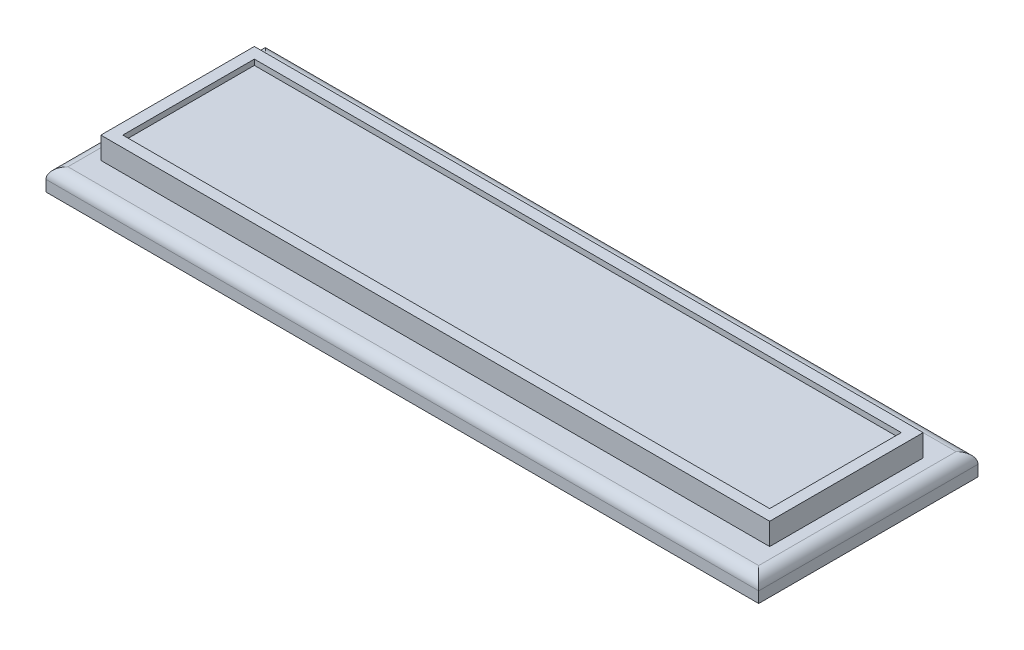
SolidWorks part; units mm, degrees
ref_plane "Plano frontal" through (0, 0, 0) normal (0, 0, 1) x (1, 0, 0)
ref_plane "Plano superior" through (0, 0, 0) normal (0, 1, 0) x (1, 0, 0)
ref_plane "Plano direito" through (0, 0, 0) normal (1, 0, 0) x (0, 0, -1)
sketch "Esboço1" plane through (0, 0, 0) normal (0, 1, 0) x (1, 0, 0)
  line L1 (0, 0) -> (65, 0)
  line L2 (0, 0) -> (0, -20)
  line L3 (0, -20) -> (65, -20)
  line L4 (65, 0) -> (65, -20)
  dimension "D1" = 65
  dimension "D2" = 20
extrude "Ressalto-extrusão1" add sketch "Esboço1" along normal blind 2
sketch "Esboço2" plane through (0, 2, 0) normal (0, 1, 0) x (1, 0, 0)
  line L1 (2, -3) -> (63, -3)
  line L2 (2, -3) -> (2, -17)
  line L3 (2, -17) -> (63, -17)
  line L4 (63, -3) -> (63, -17)
  dimension "D1" = 3
  dimension "D2" = 3
  dimension "D3" = 2
  dimension "D4" = 2
extrude "Ressalto-extrusão2" add sketch "Esboço2" along normal blind 2
sketch "Esboço3" plane through (0, 4, 0) normal (0, 1, 0) x (1, 0, 0)
  line L1 (3, -3.9962) -> (62, -3.9962)
  line L2 (3, -3.9962) -> (3, -16)
  line L3 (3, -16) -> (62, -16)
  line L4 (62, -3.9962) -> (62, -16)
  dimension "D1" = 1
  dimension "D2" = 1
  dimension "D3" = 1
extrude "Corte-extrusão1" cut sketch "Esboço3" against normal blind 0.5 contours L2 L3 L4 L1
fillet "Filete1" radius 1 4 edges at (0, 2, 10) (65, 2, 10) (32.5, 2, 20) (32.5, 2, 0)
sketch "Esboço4" plane through (0, 3.5, 0) normal (0, 1, 0) x (1, 0, 0)
  text T0 "Automação Industrial"
